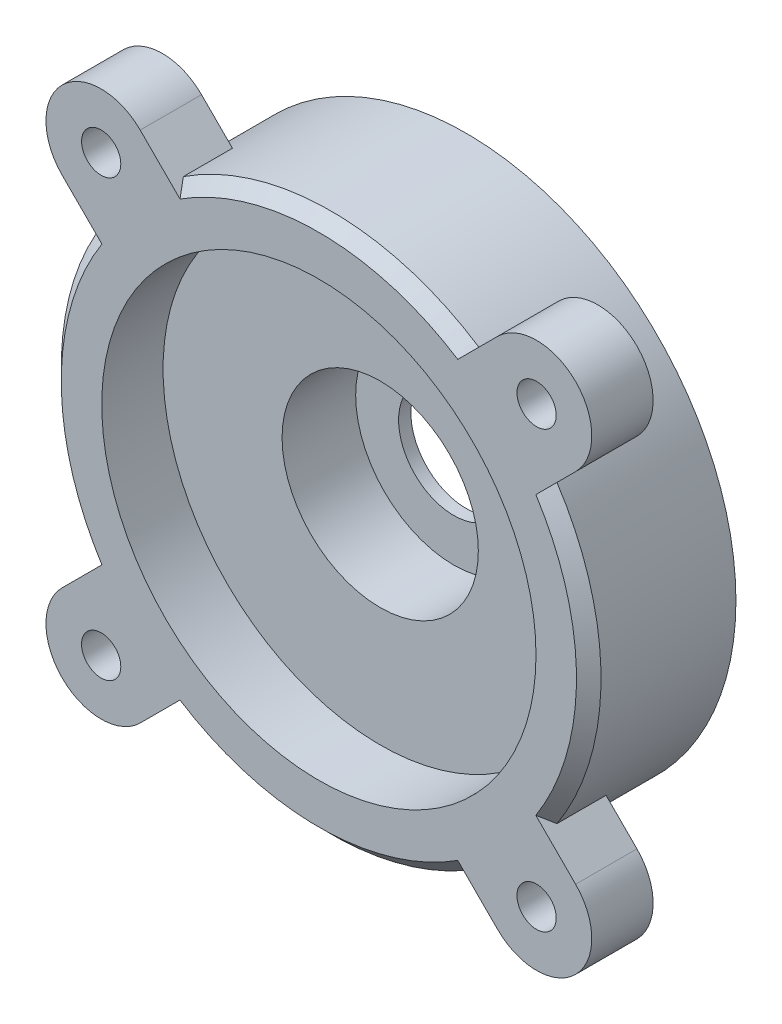
SolidWorks part; units mm, degrees
ref_plane "Front Plane" through (0, 0, 0) normal (0, 0, 1) x (1, 0, 0)
ref_plane "Top Plane" through (0, 0, 0) normal (0, 1, 0) x (1, 0, 0)
ref_plane "Right Plane" through (0, 0, 0) normal (1, 0, 0) x (0, 0, -1)
sketch "Sketch1" plane through (0, 0, 0) normal (0, 0, 1) x (1, 0, 0)
  circle A0 centre (0, 0) radius 22
  dimension "D1" = 44
extrude "Boss-Extrude1" add sketch "Sketch1" along normal mid plane 12
chamfer "Chamfer1" distance 1 angle 45 1 edges at (22, 0, 6)
sketch "Sketch8" plane through (0, 0, 6) normal (0, 0, 1) x (1, 0, 0)
  line L17 (14.5664, 20.9304) -> (11.3223, 17.6863)
  line L18 (20.9304, 14.5664) -> (17.6863, 11.3223)
  line L19 (17.6863, 11.3223) -> (11.3223, 17.6863)
  line L20 (20.9304, -14.5664) -> (17.6863, -11.3223)
  line L21 (14.5664, -20.9304) -> (11.3223, -17.6863)
  line L22 (11.3223, -17.6863) -> (17.6863, -11.3223)
  line L23 (-14.5664, -20.9304) -> (-11.3223, -17.6863)
  line L24 (-20.9304, -14.5664) -> (-17.6863, -11.3223)
  line L25 (-17.6863, -11.3223) -> (-11.3223, -17.6863)
  line L26 (-20.9304, 14.5664) -> (-17.6863, 11.3223)
  line L27 (-14.5664, 20.9304) -> (-11.3223, 17.6863)
  line L28 (-11.3223, 17.6863) -> (-17.6863, 11.3223)
  circle A2 centre (17.7484, 17.7484) radius 1.6
  circle A6 centre (17.7484, -17.7484) radius 1.6
  arc A12 (14.5664, 20.9304) -> (20.9304, 14.5664) centre (17.7484, 17.7484) cw
  circle A13 centre (0, 0) radius 21 construction
  arc A14 (20.9304, -14.5664) -> (14.5664, -20.9304) centre (17.7484, -17.7484) cw
  circle A15 centre (-17.7484, -17.7484) radius 1.6
  arc A16 (-14.5664, -20.9304) -> (-20.9304, -14.5664) centre (-17.7484, -17.7484) cw
  circle A17 centre (-17.7484, 17.7484) radius 1.6
  arc A18 (-20.9304, 14.5664) -> (-14.5664, 20.9304) centre (-17.7484, 17.7484) cw
  point P6 (17.7484, 17.7484)
  point P9 (0, 0)
  point P18 (17.7484, -17.7484)
  point P25 (-17.7484, -17.7484)
  point P31 (0, 0)
  point P33 (-17.7484, 17.7484)
  point P36 (0, 0)
  dimension "D1" = 4
extrude "Boss-Extrude2" add sketch "Sketch8" against normal blind 5
sketch "Sketch9" plane through (0, 0, 6) normal (0, 0, 1) x (1, 0, 0)
  circle A0 centre (0, 0) radius 17.7
extrude "Cut-Extrude1" cut sketch "Sketch9" against normal blind 5
sketch "Sketch10" plane through (0, 0, 1) normal (0, 0, 1) x (1, 0, 0)
  circle A0 centre (0, 0) radius 8
extrude "Cut-Extrude2" cut sketch "Sketch10" against normal blind 6
sketch "Sketch11" plane through (0, 0, -5) normal (0, 0, 1) x (1, 0, 0)
  circle A0 centre (0, 0) radius 4.5
extrude "Cut-Extrude3" cut sketch "Sketch11" against normal blind 1
